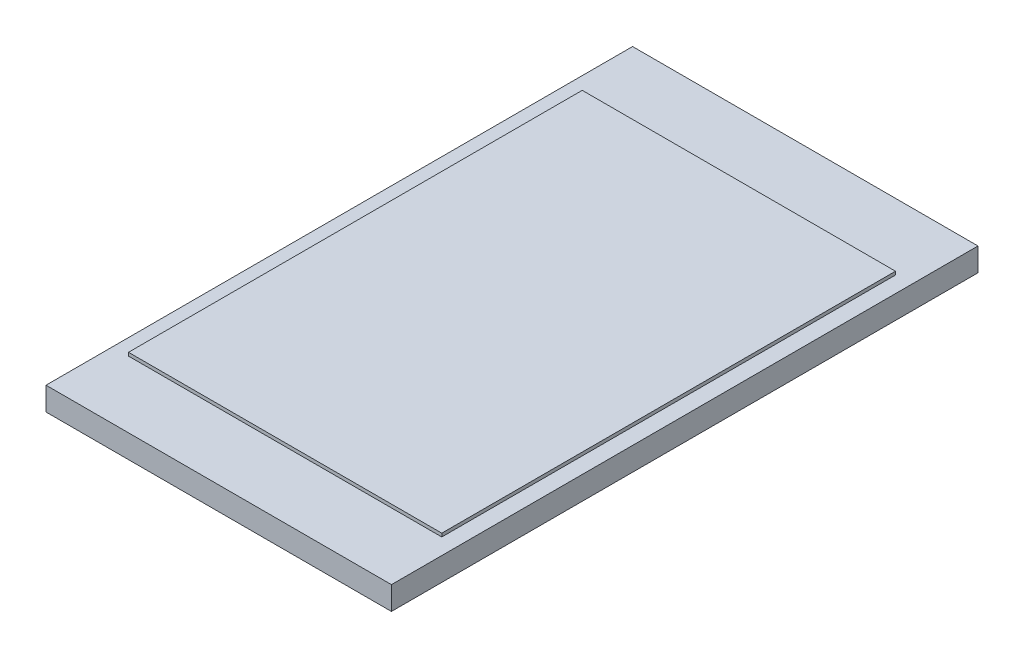
SolidWorks part; units mm, degrees
ref_plane "Front Plane" through (0, 0, 0) normal (0, 0, 1) x (1, 0, 0)
ref_plane "Top Plane" through (0, 0, 0) normal (0, 1, 0) x (1, 0, 0)
ref_plane "Right Plane" through (0, 0, 0) normal (1, 0, 0) x (0, 0, -1)
sketch "Sketch1" plane through (0, 0, 0) normal (0, 1, 0) x (1, 0, 0)
  line L1 (0, 0) -> (-132.08, 0)
  line L2 (0, 0) -> (0, 224.282)
  line L3 (0, 224.282) -> (-132.08, 224.282)
  line L4 (-132.08, 0) -> (-132.08, 224.282)
  dimension "D1" = 224.282
  dimension "D2" = 132.08
extrude "Boss-Extrude1" add sketch "Sketch1" along normal blind 8.89
sketch "Sketch2" plane through (0, 8.89, 0) normal (0, 1, 0) x (1, 0, 0)
  line L0 (-132.08, 0) -> (0, 0) construction
  line L1 (-125.9338, 198.882) -> (-6.1462, 198.882)
  line L2 (-125.9338, 198.882) -> (-125.9338, 25.4)
  line L3 (-125.9338, 25.4) -> (-6.1462, 25.4)
  line L4 (-6.1462, 198.882) -> (-6.1462, 25.4)
  line L5 (-66.04, 0) -> (-66.04, 25.4) construction
  line L6 (0, 224.282) -> (-132.08, 224.282) construction
  dimension "D1" = 25.4
  dimension "D2" = 210.82
  dimension "D3" = 25.4
extrude "Boss-Extrude2" add sketch "Sketch2" along normal blind 1.27
